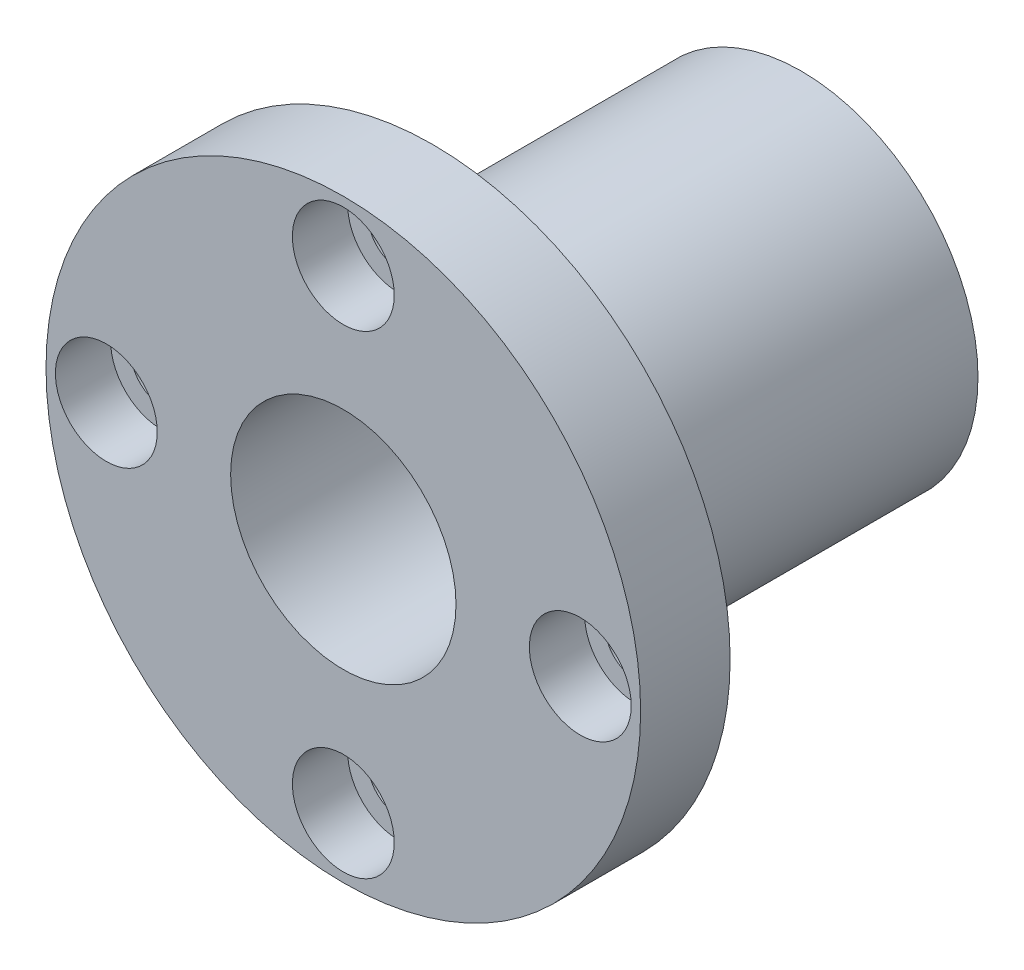
SolidWorks part; units mm, degrees
ref_plane "Plano frontal" through (0, 0, 0) normal (0, 0, 1) x (1, 0, 0)
ref_plane "Plano superior" through (0, 0, 0) normal (0, 1, 0) x (1, 0, 0)
ref_plane "Plano direito" through (0, 0, 0) normal (1, 0, 0) x (0, 0, -1)
sketch "Esboço1" plane through (0, 0, 0) normal (0, 0, 1) x (1, 0, 0)
  circle A0 centre (0, 0) radius 15.995
  dimension "D1" = 31.99
extrude "Ressalto-extrusão1" add sketch "Esboço1" along normal blind 33.35
sketch "Esboço2" plane through (0, 0, 33.35) normal (0, 0, 1) x (1, 0, 0)
  circle A2 centre (0, 0) radius 26.91
  dimension "D1" = 53.82
extrude "Ressalto-extrusão2" add sketch "Esboço2" along normal blind 8.1
sketch "Esboço3" plane through (0, 0, 41.45) normal (0, 0, 1) x (1, 0, 0)
  line L0 (0, 26.91) -> (0, -26.91) construction
  line L1 (26.91, 0) -> (-26.91, 0) construction
  circle A0 centre (0, 0) radius 26.91 construction
  circle A1 centre (21.45, 0) radius 4.61
  circle A2 centre (0, -21.45) radius 4.61
  circle A3 centre (-21.45, 0) radius 4.61
  circle A4 centre (0, 21.45) radius 4.61
  dimension "D1" = 9.22
  dimension "D2" = 5.46
  dimension "D3" = 4
extrude "Corte-extrusão1" cut sketch "Esboço3" against normal blind 5
sketch "Esboço4" plane through (0, 0, 41.45) normal (0, 0, 1) x (1, 0, 0)
  line L0 (0, 26.9759) -> (0, -26.8441) construction
  line L1 (26.91, 0.0659) -> (-26.91, 0.0659) construction
  circle A0 centre (21.45, 0) radius 2.755
  circle A1 centre (0, -21.45) radius 2.755
  circle A2 centre (-21.45, 0) radius 2.755
  circle A3 centre (0, 21.45) radius 2.755
  dimension "D1" = 5.51
  dimension "D2" = 4
extrude "Corte-extrusão2" cut sketch "Esboço4" against normal up to surface (8.1 mm away) up to face at (26.91, 0, 33.35)
sketch "Esboço5" plane through (0, 0, 41.45) normal (0, 0, 1) x (1, 0, 0)
  circle A0 centre (0, 0) radius 10.2
  dimension "D1" = 20.4
extrude "Corte-extrusão3" cut sketch "Esboço5" against normal up to surface (41.45 mm away) up to face at (15.995, 0, 0)
